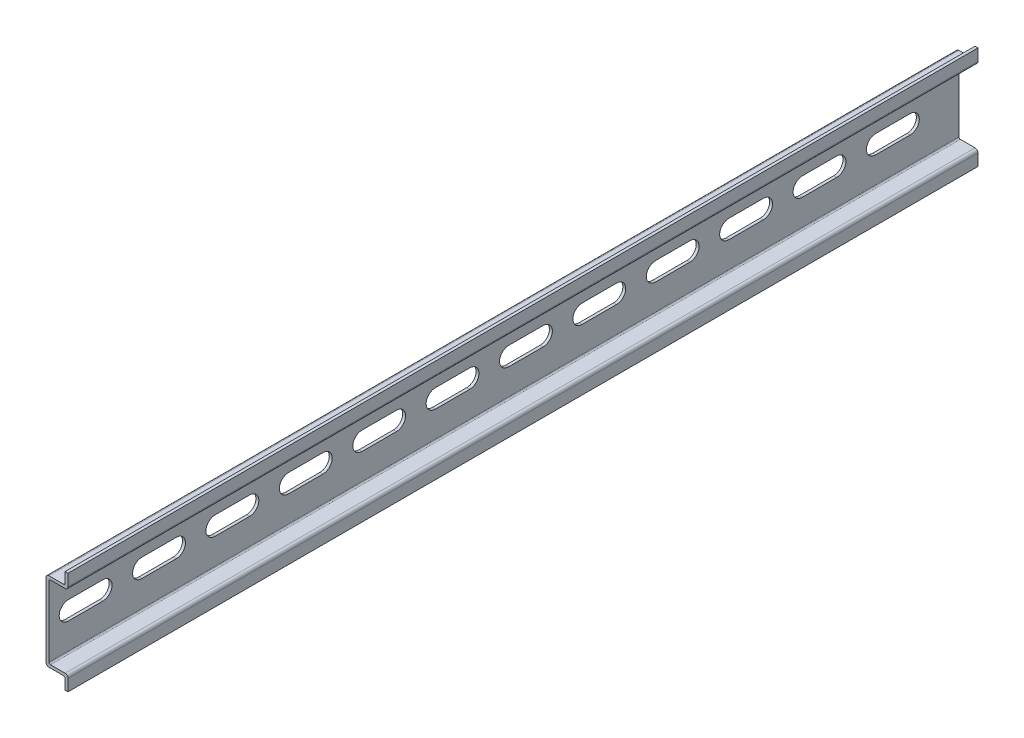
SolidWorks part; units mm, degrees
ref_plane "Front Plane" through (0, 0, 0) normal (0, 0, 1) x (1, 0, 0)
ref_plane "Top Plane" through (0, 0, 0) normal (0, 1, 0) x (1, 0, 0)
ref_plane "Right Plane" through (0, 0, 0) normal (1, 0, 0) x (0, 0, -1)
sketch "Sketch1" plane through (0, 0, 0) normal (0, 0, 1) x (1, 0, 0)
  line L0 (0, 0) -> (7.5, 0) construction
  line L1 (0, 17.5) -> (7.5, 17.5) construction
  line L2 (0, 17.5) -> (0, -17.5) construction
  line L3 (0, -17.5) -> (7.5, -17.5) construction
  line L4 (7.5, 17.5) -> (7.5, -17.5) construction
  line L5 (7.5, 17.5) -> (6.5, 17.5)
  line L6 (6.5, 17.5) -> (6.5, 14)
  line L7 (6, 13.5) -> (1, 13.5)
  line L8 (0, 12.5) -> (0, -12.5)
  line L9 (7.5, 17.5) -> (7.5, 13.5)
  line L10 (6.5, 12.5) -> (1.5, 12.5)
  line L11 (1, 12) -> (1, -12)
  line L12 (6.5, -12.5) -> (1.5, -12.5)
  line L13 (7.5, -17.5) -> (7.5, -13.5)
  line L14 (6, -13.5) -> (1, -13.5)
  line L15 (6.5, -17.5) -> (6.5, -14)
  line L16 (7.5, -17.5) -> (6.5, -17.5)
  line L17 (6.3536, 13.6464) -> (7.2071, 12.7929) construction
  line L18 (1.1464, 12.3536) -> (0.2929, 13.2071) construction
  arc A0 (1.5, 12.5) -> (1, 12) centre (1.5, 12) ccw
  arc A1 (1, 13.5) -> (0, 12.5) centre (1, 12.5) ccw
  arc A2 (7.5, 13.5) -> (6.5, 12.5) centre (6.5, 13.5) cw
  arc A3 (6, 13.5) -> (6.5, 14) centre (6, 14) ccw
  arc A4 (1, -13.5) -> (0, -12.5) centre (1, -12.5) cw
  arc A5 (1.5, -12.5) -> (1, -12) centre (1.5, -12) cw
  arc A6 (7.5, -13.5) -> (6.5, -12.5) centre (6.5, -13.5) ccw
  arc A7 (6, -13.5) -> (6.5, -14) centre (6, -14) cw
  dimension "D5" = 1
  dimension "D6" = 0.5
  dimension "D1" = 35
  dimension "D2" = 7.5
  dimension "D3" = 1
  dimension "D4" = 27
extrude "Boss-Extrude1" add sketch "Sketch1" along normal mid plane 310
sketch "Sketch2" plane through (0, 0, 0) normal (1, 0, 0) x (0, 0, -1)
  line L0 (-148.35, 0) -> (-136.65, 0) construction
  line L1 (-148.35, 3.15) -> (-136.65, 3.15)
  line L2 (-148.35, -3.15) -> (-136.65, -3.15)
  line L3 (-142.5, 0) -> (-155, 0) construction
  line L4 (-155, 12.5) -> (-155, -12.5) construction
  line L5 (-142.5, 0) -> (-117.5, 0) construction
  line L6 (-117.5, 0) -> (-92.5, 0) construction
  arc A0 (-148.35, 3.15) -> (-148.35, -3.15) centre (-148.35, 0) ccw
  arc A1 (-136.65, -3.15) -> (-136.65, 3.15) centre (-136.65, 0) ccw
  point P2 (-142.5, 0)
  dimension "D1" = 6.3
  dimension "D2" = 18
  dimension "D4" = 12.5
  dimension "D3" = 25
extrude "Cut-Extrude1" cut sketch "Sketch2" along normal up to vertex (7.5 mm away) up to point (7.5, 0, 0)
pattern_linear "LPattern1" count 12 spacing 25 along (0, 0, -1) of "Cut-Extrude1"
equation "\"D4@Sketch2\" = \"D3@Sketch2\" / 2"
equation "\"D3@LPattern1\" = \"D3@Sketch2\""
equation "\"D1@LPattern1\" = \"D1@Boss-Extrude1\" / \"D3@LPattern1\""
